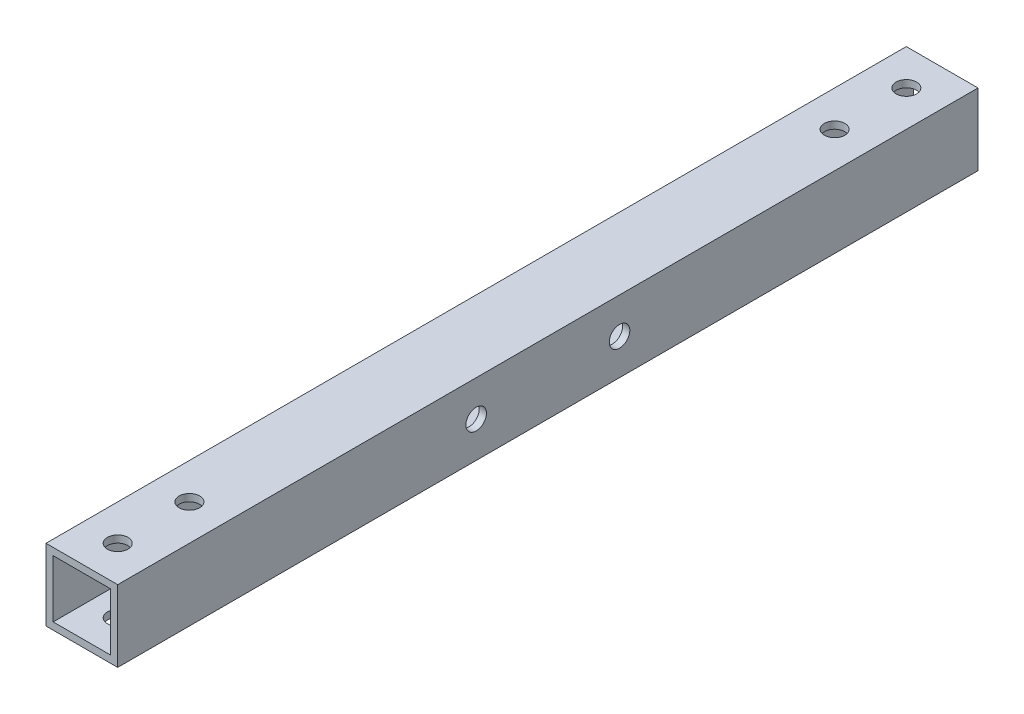
SolidWorks part; units mm, degrees
material "5052-H34"
ref_plane "正面" through (0, 0, 0) normal (0, 0, 1) x (1, 0, 0)
ref_plane "平面" through (0, 0, 0) normal (0, 1, 0) x (1, 0, 0)
ref_plane "右側面" through (0, 0, 0) normal (1, 0, 0) x (0, 0, -1)
sketch "ｽｹｯﾁ1" plane through (0, 0, 0) normal (0, 0, 1) x (1, 0, 0)
  line L1 (-7.5, 7.5) -> (7.5, 7.5)
  line L2 (-7.5, 7.5) -> (-7.5, -7.5)
  line L3 (-7.5, -7.5) -> (7.5, -7.5)
  line L4 (7.5, 7.5) -> (7.5, -7.5)
  line L5 (-7.5, 7.5) -> (7.5, -7.5) construction
  line L6 (-7.5, -7.5) -> (7.5, 7.5) construction
  point P0 (0, 0)
  dimension "D1" = 15
  dimension "D2" = 15
extrude "押し出し-薄板1" add sketch "ｽｹｯﾁ1" along normal blind 180 thin
sketch "ｽｹｯﾁ3" plane through (7.5, 0, 0) normal (1, 0, 0) x (0, 0, -1)
  line L0 (-90, 7.5) -> (-90, -7.5) construction
  line L1 (-180, 7.5) -> (0, 7.5) construction
  line L2 (-180, -7.5) -> (0, -7.5) construction
  line L3 (-90, 0) -> (-75, 0) construction
  circle A0 centre (-75, 0) radius 2.15
  circle A1 centre (-105, 0) radius 2.15
  dimension "D1" = 4.3
  dimension "D2" = 30
extrude "ｶｯﾄ - 押し出し2" cut sketch "ｽｹｯﾁ3" against normal through all
sketch "ｽｹｯﾁ4" plane through (0, 7.5, 0) normal (0, 1, 0) x (1, 0, 0)
  line L0 (-7.5, -90) -> (7.5, -90) construction
  line L1 (-7.5, -180) -> (-7.5, 0) construction
  line L2 (7.5, -180) -> (7.5, 0) construction
  line L3 (0, -90) -> (0, -22.5) construction
  line L4 (0, -22.5) -> (0, -7.5) construction
  circle A0 centre (0, -22.5) radius 2.15
  circle A1 centre (0, -157.5) radius 2.15
  circle A2 centre (0, -7.5) radius 2.15
  circle A3 centre (0, -172.5) radius 2.15
  circle A4 centre (0, -157.5) radius 2.15
  dimension "D1" = 4.3
  dimension "D2" = 15
  dimension "D3" = 7.5
extrude "ｶｯﾄ - 押し出し3" cut sketch "ｽｹｯﾁ4" against normal through all contours A2 | A0 | A3 | A1
